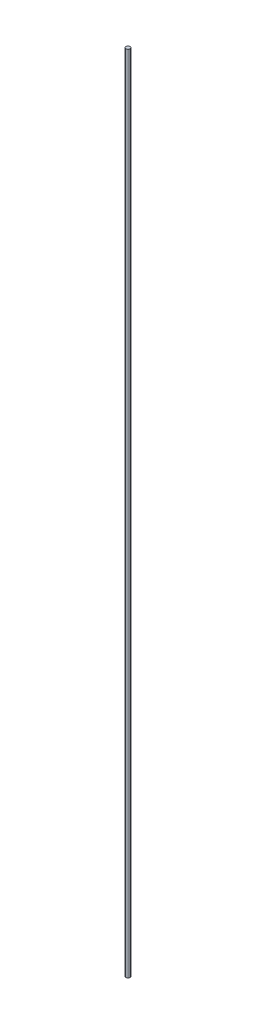
SolidWorks part; units mm, degrees
ref_plane "Front Plane" through (0, 0, 0) normal (0, 0, 1) x (1, 0, 0)
ref_plane "Top Plane" through (0, 0, 0) normal (0, 1, 0) x (1, 0, 0)
ref_plane "Right Plane" through (0, 0, 0) normal (1, 0, 0) x (0, 0, -1)
sketch "Sketch2" plane through (0, 0, 0) normal (0, 1, 0) x (1, 0, 0)
  circle A0 centre (0, 0) radius 3.175
  dimension "D1" = 6.35
extrude "Boss-Extrude1" add sketch "Sketch2" along normal blind 1270
